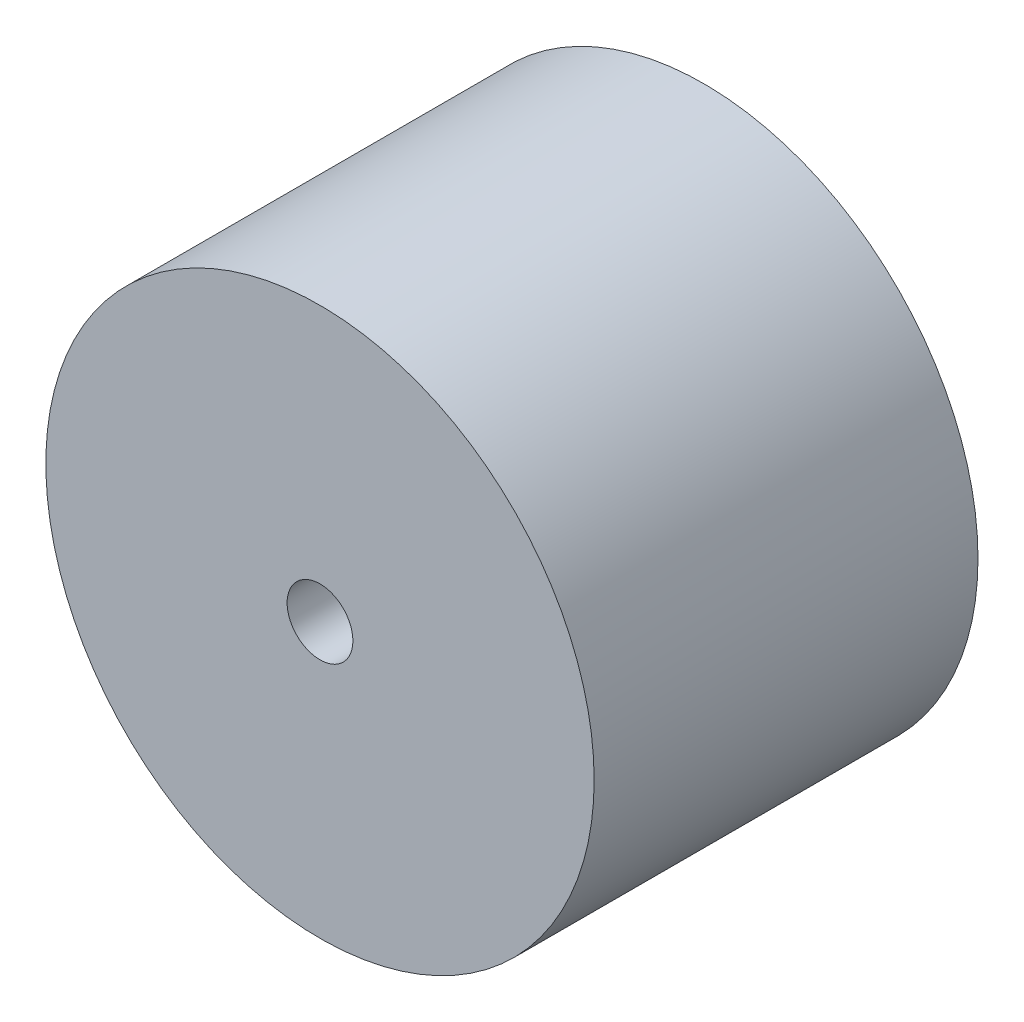
SolidWorks part; units mm, degrees
ref_plane "Plan de face" through (0, 0, 0) normal (0, 0, 1) x (1, 0, 0)
ref_plane "Plan de dessus" through (0, 0, 0) normal (0, 1, 0) x (1, 0, 0)
ref_plane "Plan de droite" through (0, 0, 0) normal (1, 0, 0) x (0, 0, -1)
sketch "Esquisse1" plane through (0, 0, 0) normal (0, 0, 1) x (1, 0, 0)
  circle A0 centre (0, 0) radius 25
  circle A1 centre (0, 0) radius 3
  dimension "D1" = 50
  dimension "D2" = 6
extrude "Boss.-Extru.1" add sketch "Esquisse1" along normal mid plane 35
